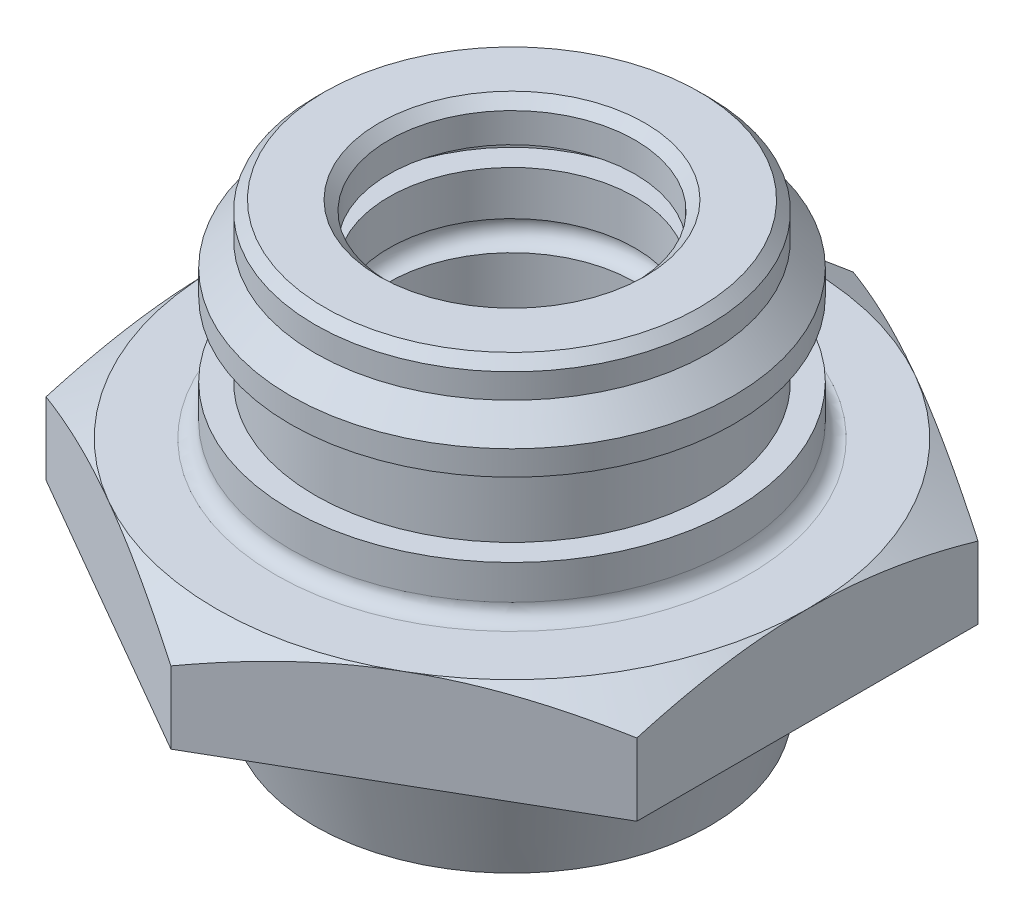
SolidWorks part; units mm, degrees
ref_plane "Front Plane" through (0, 0, 0) normal (0, 0, 1) x (1, 0, 0)
ref_plane "Top Plane" through (0, 0, 0) normal (0, 1, 0) x (1, 0, 0)
ref_plane "Right Plane" through (0, 0, 0) normal (1, 0, 0) x (0, 0, -1)
sketch "Sketch1" plane through (0, 0, 0) normal (0, 1, 0) x (1, 0, 0)
  line L1 (0, 69.282) -> (-60, 34.641)
  line L2 (-60, 34.641) -> (-60, -34.641)
  line L3 (-60, -34.641) -> (0, -69.282)
  line L4 (0, -69.282) -> (60, -34.641)
  line L5 (60, -34.641) -> (60, 34.641)
  line L6 (60, 34.641) -> (0, 69.282)
  circle A0 centre (0, 0) radius 60 construction
  dimension "D1" = 120
extrude "Boss-Extrude1" add sketch "Sketch1" along normal blind 20
sketch "Sketch2" plane through (0, 0, 0) normal (0, 0, 1) x (1, 0, 0)
  line L0 (0, 20) -> (0, 62)
  line L1 (0, 62) -> (40, 62)
  line L2 (0, 20) -> (0, -30)
  line L3 (0, 20) -> (45, 20)
  line L4 (0, 20) -> (60, 20) construction
  line L5 (45, 20) -> (45, 30)
  line L6 (45, 30) -> (40, 30)
  line L7 (40, 30) -> (40, 45)
  line L8 (40, 45) -> (45, 45)
  line L9 (45, 45) -> (45, 50)
  line L10 (45, 50) -> (40, 55)
  line L11 (40, 55) -> (40, 62)
  line L12 (45, 20) -> (45, -10)
  line L13 (45, -10) -> (39.641, -30)
  line L14 (0, -30) -> (39.641, -30)
  dimension "D1" = 39.641
  dimension "D2" = 40
  dimension "D3" = 45
  dimension "D4" = 30
  dimension "D5" = 45
  dimension "D6" = 10
  dimension "D7" = 55
  dimension "D8" = 62
  dimension "D10" = 30
revolve "Revolve1" add sketch "Sketch2" angle 360 about L0
sketch "Sketch3" plane through (0, 0, 0) normal (0, 0, 1) x (1, 0, 0)
  line L0 (0, 62) -> (0, -30)
  line L3 (25, -30) -> (25, 6.3397)
  line L4 (25, 0) -> (25, 6.3397)
  line L6 (25, 20) -> (25, 35)
  line L7 (30, 20) -> (25, 20)
  line L9 (32.5, 10.6699) -> (25, 6.3397)
  line L11 (25, 62) -> (25, 54)
  line L12 (25, 54) -> (30, 54)
  line L13 (30, 54) -> (30, 50)
  line L14 (30, 50) -> (25, 50)
  line L16 (25, 50) -> (25, 41)
  line L17 (25, 54) -> (25, 62)
  line L18 (25, 41) -> (25, 50)
  line L19 (0, 62) -> (25, 62)
  line L20 (0, -30) -> (25, -30)
  arc A0 (32.5, 10.6699) -> (30, 20) centre (30, 15) ccw
  arc A1 (25, 35) -> (25, 41) centre (25, 38) ccw
  dimension "D1" = 5
  dimension "D2" = 3
  dimension "D3" = 25
  dimension "D4" = 32.5
  dimension "D5" = 6.3397
  dimension "D9" = 38
  dimension "D10" = 50
  dimension "D11" = 54
  dimension "D12" = 62
  dimension "D13" = 30
revolve "Cut-Revolve1" cut sketch "Sketch3" angle 360 about L0
ref_plane "Plane2" through (0, 0, 0) normal (0.5, 0, 0.866) x (0, -1, 0)
sketch "Sketch5" plane through (0, 20, 0) normal (0, 1, 0) x (1, 0, 0)
  circle A0 centre (0, 0) radius 60
extrude "Cut-Extrude1" cut sketch "Sketch5" against normal blind 20 draft 60 flip side to cut
fillet "Fillet1" radius 3 2 edges at (0, 20, 45) (0, 0, 45)
chamfer "Chamfer1" distance 2 angle 45 4 edges at (40, 62, 0) (39.641, -30, 0) (0, 62, 25) (0, -30, 25)
